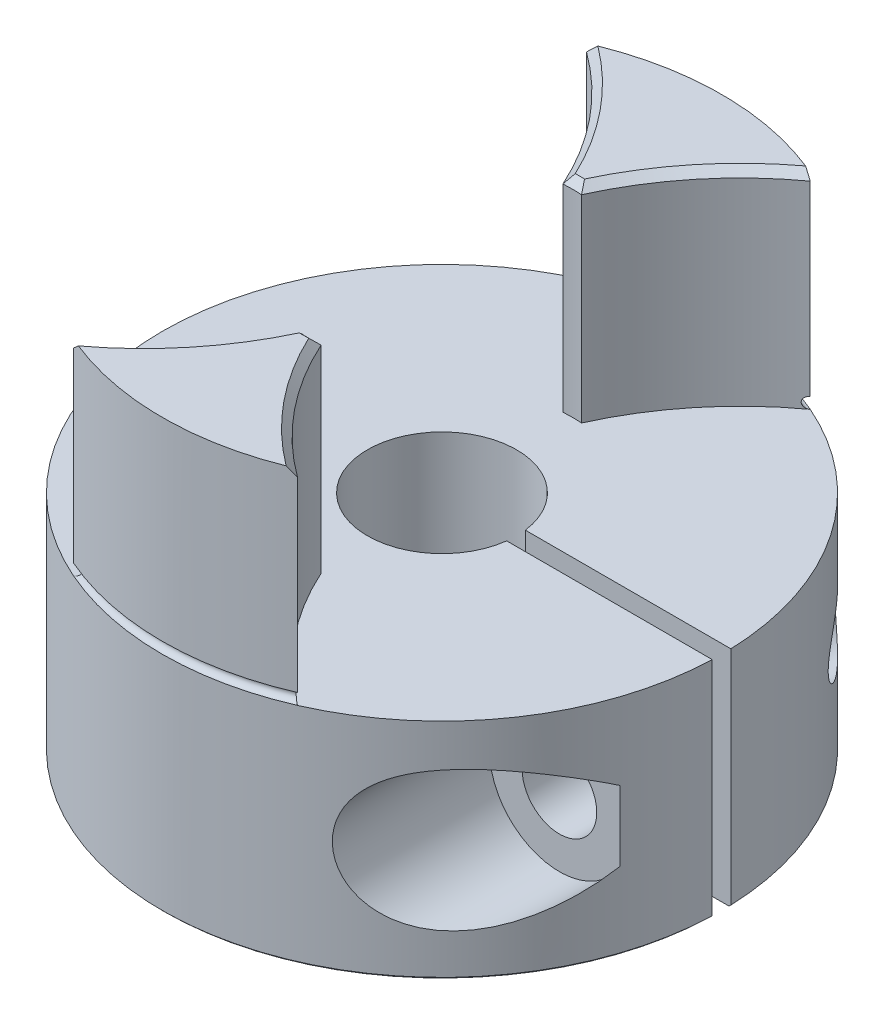
SolidWorks part; units mm, degrees
material "1060 Alloy"
ref_plane "Front" through (0, 0, 0) normal (0, 0, 1) x (1, 0, 0)
ref_plane "Top" through (0, 0, 0) normal (0, 1, 0) x (1, 0, 0)
ref_plane "Right" through (0, 0, 0) normal (1, 0, 0) x (0, 0, -1)
sketch "Sketch1" plane through (0, 0, 0) normal (0, 1, 0) x (1, 0, 0)
  circle A0 centre (0, 0) radius 15
extrude "Boss-Extrude1" add sketch "Sketch1" along normal mid plane 23
sketch "Sketch2" plane through (0, 11.5, 0) normal (0, 1, 0) x (1, 0, 0)
  circle A0 centre (0, 0) radius 7
  dimension "D1" = 14
extrude "Cut-Extrude1" cut sketch "Sketch2" against normal blind 23
sketch "Sketch3" plane through (0, 11.5, 0) normal (0, 1, 0) x (1, 0, 0)
  line L0 (-19.0209, 0) -> (26.8019, 0) construction
  line L1 (0, 17.1133) -> (0, -22.8638) construction
  line L2 (6, 13.7477) -> (6, 19.4636) construction
  circle A0 centre (16, 0) radius 17
  circle A1 centre (0, 0) radius 15 construction
  circle A2 centre (0, 0) radius 15 construction
  dimension "D2" = 34
  dimension "D1" = 6
extrude "Cut-Extrude2" cut sketch "Sketch3" against normal blind 11
sketch "Sketch4" plane through (0, 11.5, 0) normal (0, 1, 0) x (1, 0, 0)
  line L0 (0, 15) -> (0, -15) construction
  line L1 (-15, 0) -> (15, 0) construction
  arc A0 (6, 13.7477) -> (6, -13.7477) centre (0, 0) ccw construction
  arc A1 (6, -13.7477) -> (6, 13.7477) centre (0, 0) ccw construction
  arc A4 (0.5, -6.9821) -> (6, -13.7477) centre (16, 0) ccw construction
  arc A6 (0.5, 6.9821) -> (0.5, -6.9821) centre (0, 0) ccw construction
  arc A8 (-6, 13.7477) -> (-6, -13.7477) centre (0, 0) ccw
  arc A9 (-0.5, -6.9821) -> (-6, -13.7477) centre (-16, 0) cw
  arc A10 (-6, 13.7477) -> (-0.5, 6.9821) centre (-16, 0) cw
  arc A11 (-0.5, 6.9821) -> (-0.5, -6.9821) centre (0, 0) ccw
extrude "Cut-Extrude3" cut sketch "Sketch4" against normal blind 11
sketch "Sketch5" plane through (0, 0.5, 0) normal (0, 1, 0) x (1, 0, 0)
  line L0 (0, 0) -> (23.6149, 0) construction
  line L2 (3.7246, 0.5) -> (19.8903, 0.5)
  line L3 (3.7246, 0.5) -> (3.7246, -0.5)
  line L4 (3.7246, -0.5) -> (19.8903, -0.5)
  line L5 (19.8903, 0.5) -> (19.8903, -0.5)
  line L6 (3.7246, 0.5) -> (19.8903, -0.5) construction
  line L7 (3.7246, -0.5) -> (19.8903, 0.5) construction
  point P3 (11.8074, 0)
  dimension "D1" = 1
extrude "Cut-Extrude4" cut sketch "Sketch5" against normal blind 21
sketch "Sketch6" plane through (0, 0, 0) normal (0, 0, 1) x (1, 0, 0)
  line L0 (0, 17.6778) -> (0, -16.8659) construction
  line L1 (-15, -5.5) -> (14.9917, -5.5) construction
  line L2 (-15, 0.5) -> (-15, -11.5) construction
  line L3 (14.9917, -11.5) -> (14.9917, 0.5) construction
  circle A0 centre (11, -5.5) radius 2
  dimension "D1" = 11
  dimension "D2" = 4
extrude "Cut-Extrude5" cut sketch "Sketch6" along normal blind 21
sketch "Sketch7" plane through (0, 0, 0.5) normal (0, 0, -1) x (-1, 0, 0)
  circle A0 centre (-11, -5.5) radius 3.75
extrude "Cut-Extrude6" cut sketch "Sketch7" against normal blind 21 from offset 4.2 offset against normal yes
hole_wizard "M4 Tapped Hole1" positions "Sketch8" profile "Sketch9" tap size "M4" standard "ISO"
sketch "Sketch8" plane through (0, 0, -0.5) normal (0, 0, 1) x (1, 0, 0)
  point P0 (11, -5.5)
sketch "Sketch9" plane through (11, -5.5, -0.5) normal (1, 0, 0) x (0, -1, 0)
  line L0 (0, 0) -> (0, 21.0914)
  line L1 (0, 21.0914) -> (1.65, 20.1)
  line L2 (1.65, 20.1) -> (1.65, 0)
  line L5 (1.65, 0) -> (0, 0)
  line L10 (0, 21.0914) -> (-1.65, 20.1) construction
  line L11 (0, -6.35) -> (0, 107.95) construction
  dimension "Tap Drill Dia." = 3.3
  dimension "Tap Drill Depth" = 20.1
  dimension "Drill Angle" = 118
cosmetic thread "Hole Thread1" parameters "D1"=11.2293, "D2"=4
chamfer "Chamfer1" distance 0.4 angle 45 6 edges at (2.8089, 11.5, 10.7235) (2.8089, 11.5, -10.7235) (-2.8089, 11.5, 10.7235) (-2.8089, 11.5, -10.7235) (0, 11.5, 7) (0, 11.5, -7)
sketch "Sketch10" plane through (0, 0, 0) normal (1, 0, 0) x (0, 0, -1)
  line L0 (0.5, 0.5) -> (17.5553, 0.5) construction
  line L1 (15, -11.5) -> (15, 11.5) construction
  line L2 (0, 3.3604) -> (0, -12.7174) construction
  circle A0 centre (15, 0.8) radius 0.3
  dimension "D1" = 0.6
revolve "Cut-Revolve1" cut sketch "Sketch10" angle 360 about L2
chamfer "Chamfer2" distance 0.1 angle 45 1 edges at (-15, -11.5, 0)
sketch "Çizim1" plane through (0, 0.5, 0) normal (0, 1, 0) x (1, 0, 0)
  line L0 (6.9821, 0.5) -> (3.9686, 0.5)
  line L1 (6.9821, -0.5) -> (3.9686, -0.5)
  arc A3 (3.9686, 0.5) -> (3.9686, -0.5) centre (0, 0) ccw
  arc A4 (6.9821, 0.5) -> (6.9821, -0.5) centre (0, 0) ccw
  dimension "D1" = 8
extrude "Yükseklik-Ekstrüzyon1" add sketch "Çizim1" against normal up to surface (12 mm away) up to face at (-0.0066, -11.5, 0)
